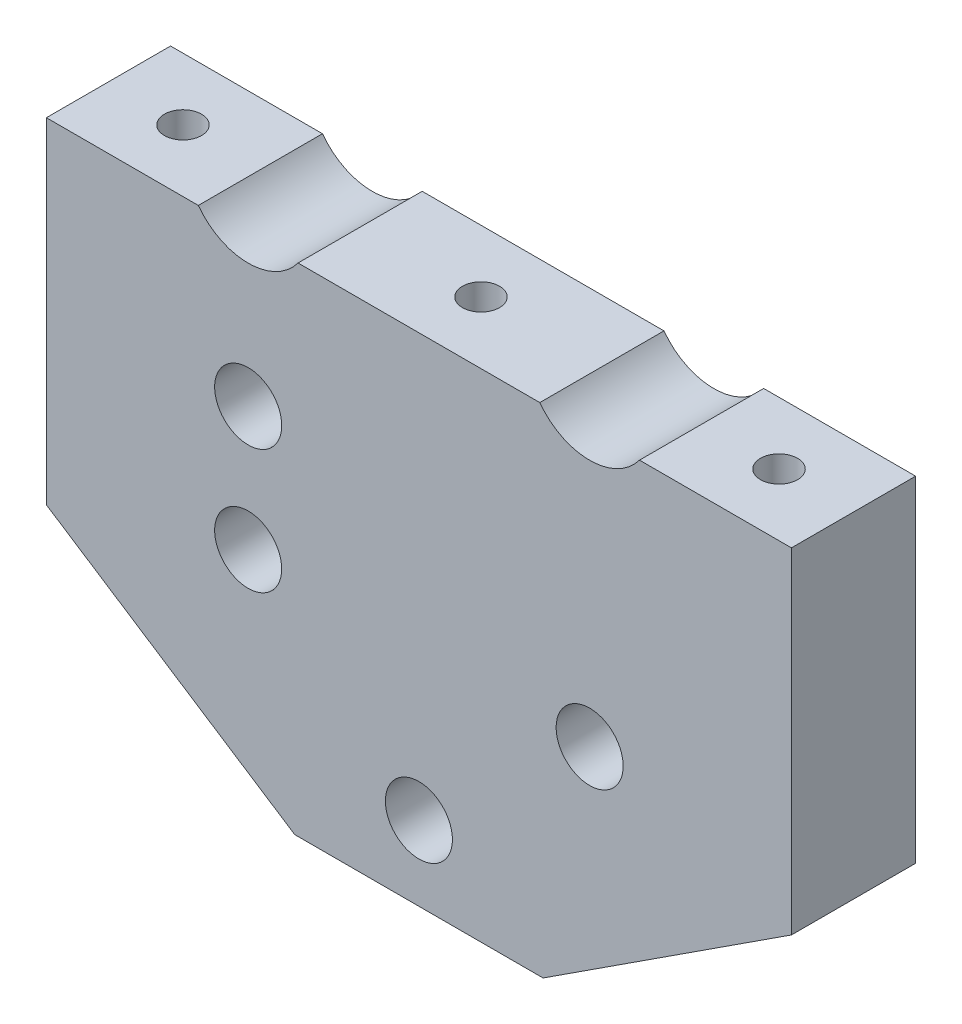
SolidWorks part; units mm, degrees
material "6061-T6 (SS)"
ref_plane "Front Plane" through (0, 0, 0) normal (0, 0, 1) x (1, 0, 0)
ref_plane "Top Plane" through (0, 0, 0) normal (0, 1, 0) x (1, 0, 0)
ref_plane "Right Plane" through (0, 0, 0) normal (1, 0, 0) x (0, 0, -1)
sketch "Sketch1" plane through (0, 0, 0) normal (0, 0, 1) x (1, 0, 0)
  line L0 (-38.1, 17.145) -> (-38.1, 24.7142) construction
  line L2 (-38.1, -17.145) -> (-38.1, 17.145)
  line L3 (-38.1, 17.145) -> (-22.5615, 17.145)
  line L4 (38.1, -17.145) -> (38.1, 17.145)
  line L5 (-38.1, -17.145) -> (38.1, 17.145) construction
  line L6 (-38.1, 17.145) -> (38.1, -17.145) construction
  line L7 (-38.1, 24.7142) -> (38.1, 24.7142) construction
  line L8 (-38.1, 24.7142) -> (-38.1, 33.6042) construction
  line L9 (-38.1, 33.6042) -> (38.1, 33.6042) construction
  line L10 (-38.1, 20.9296) -> (38.1, 20.9296) construction
  line L11 (0, 33.6042) -> (0, -33.655) construction
  line L12 (-12.3635, 17.145) -> (12.3635, 17.145)
  line L13 (22.5615, 17.145) -> (38.1, 17.145)
  line L14 (-38.1, -17.145) -> (-12.7, -33.655)
  line L15 (-12.7, -33.655) -> (12.7, -33.655)
  line L16 (38.1, -17.145) -> (12.7, -33.655)
  arc A0 (-11.1125, 20.9296) -> (-23.8125, 20.9296) centre (-17.4625, 20.9296) ccw construction
  arc A1 (22.5615, 17.145) -> (12.3635, 17.145) centre (17.4625, 20.9296) cw
  arc A2 (-22.5615, 17.145) -> (-12.3635, 17.145) centre (-17.4625, 20.9296) ccw
  arc A3 (11.1125, 20.9296) -> (23.8125, 20.9296) centre (17.4625, 20.9296) cw construction
  circle A4 centre (-17.4625, -10.795) radius 3.429
  circle A5 centre (17.4625, -10.795) radius 3.429
  circle A6 centre (-17.4625, 1.905) radius 3.429
  circle A7 centre (0, -26.035) radius 3.429
  point P0 (0, 0)
  dimension "D5" = 12.7
  dimension "D6" = 34.925
  dimension "D7" = 7.62
  dimension "D8" = 6.858
  dimension "D9" = 6.858
  dimension "D10" = 6.858
  dimension "D1" = 76.2
  dimension "D2" = 34.29
  dimension "D3" = 8.89
  dimension "D4" = 7.5692
  dimension "D12" = 25.4
extrude "Boss-Extrude1" add sketch "Sketch1" along normal blind 12.7
sketch "Sketch2" plane through (0, 17.145, 0) normal (0, 1, 0) x (1, 0, 0)
  line L0 (-38.1, -6.35) -> (38.1, -6.35) construction
  line L1 (-38.1, -12.7) -> (-38.1, 0) construction
  line L2 (38.1, -12.7) -> (38.1, 0) construction
  point P6 (0, -6.35)
  point P7 (30.48, -6.35)
  point P8 (-30.48, -6.35)
  dimension "D1" = 7.62
  dimension "D2" = 7.62
hole_wizard "#10-24 Tapped Hole1" positions "Sketch2" profile "Sketch3" tap size "#10-24" standard "ANSI Inch"
sketch "Sketch3" plane through (-30.48, 17.145, 6.35) normal (1, 0, 0) x (0, 0, 1)
  line L0 (0, 0) -> (0, 20.1908)
  line L1 (0, 20.1908) -> (1.8986, 19.05)
  line L2 (1.8986, 19.05) -> (1.8986, 0)
  line L5 (1.8986, 0) -> (0, 0)
  line L10 (0, 20.1908) -> (-1.8987, 19.05) construction
  line L11 (0, -6.35) -> (0, 107.95) construction
  dimension "Tap Drill Dia." = 3.7973
  dimension "Tap Drill Depth" = 19.05
  dimension "Drill Angle" = 118
cosmetic thread "Hole Thread1" parameters "D1"=9.652, "D2"=4.826
cosmetic thread "Hole Thread2" parameters "D1"=9.652, "D2"=4.826
cosmetic thread "Hole Thread3" parameters "D1"=9.652, "D2"=4.826
